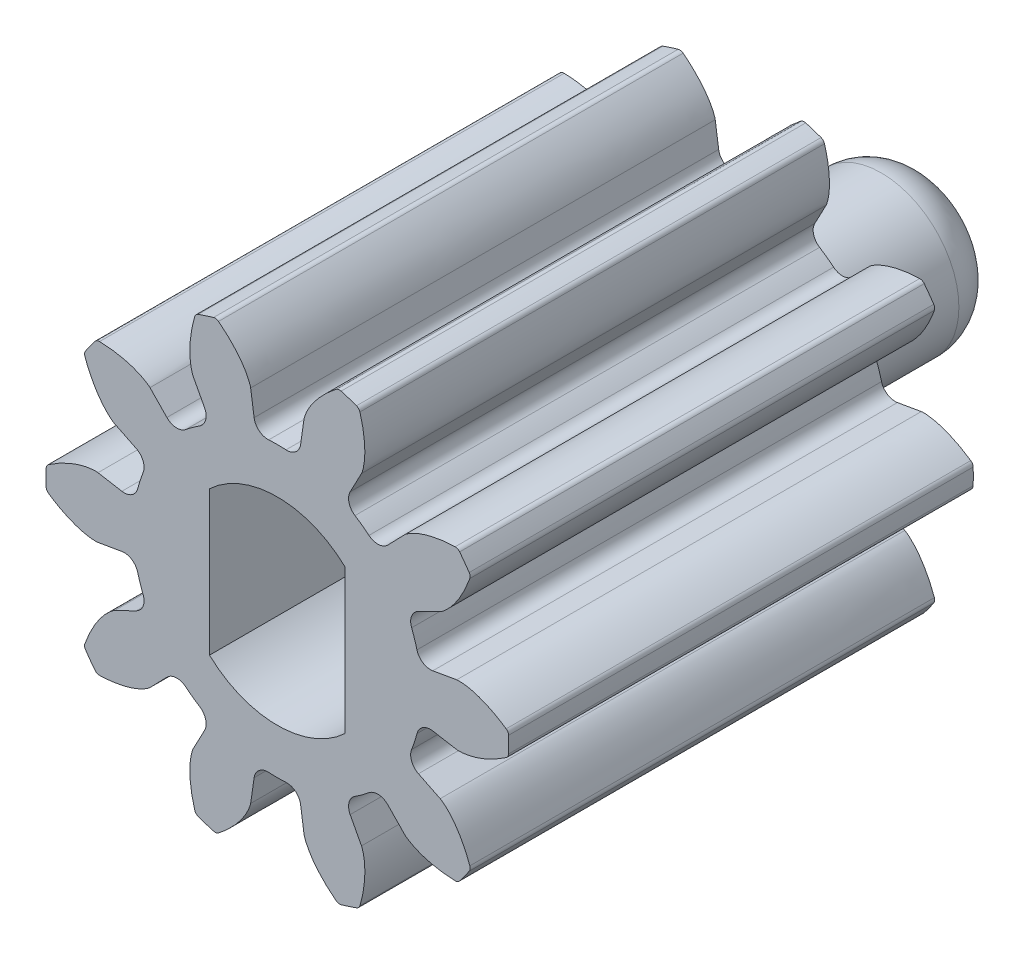
SolidWorks part; units mm, degrees
material "ABS"
ref_plane "Front" through (0, 0, 0) normal (0, 0, 1) x (1, 0, 0)
ref_plane "Top" through (0, 0, 0) normal (0, 1, 0) x (1, 0, 0)
ref_plane "Right" through (0, 0, 0) normal (1, 0, 0) x (0, 0, -1)
sketch "Sketch1" plane through (0, 0, 0) normal (0, 0, 1) x (1, 0, 0)
  circle A0 centre (0, 0) radius 6.35
extrude "Boss-Extrude1" add sketch "Sketch1" along normal blind 12.7
sketch "Sketch3" plane through (0, 0, 0) normal (0, 0, 1) x (1, 0, 0)
  line L0 (0, 0) -> (43.7181, 0) construction
  line L2 (0, 0) -> (-0.5624, 3.9287) construction
  line L3 (0, 0) -> (0.5624, 3.9287) construction
  line L4 (0.5624, 3.9287) -> (0.7046, 4.9224) construction
  line L5 (0, 0) -> (0, 61.276) construction
  line L6 (-0.5624, 3.9287) -> (-0.7046, 4.9224) construction
  circle A0 centre (0, 0) radius 6.35 construction
  circle A1 centre (0, 0) radius 5.2917 construction
  circle A2 centre (0, 0) radius 4.9725 construction
  arc A3 (0.5624, 3.9287) -> (-0.5624, 3.9287) centre (0, 0) ccw construction
  arc A5 (1.6642, 6.128) -> (-1.6642, 6.128) centre (0, 0) ccw
  spline S0 degree 4 poles (-0.7046, 4.9224) (-0.705, 4.9247) (-0.7061, 4.9311) (-0.7087, 4.9431) (-0.7137, 4.9626) (-0.721, 4.9872) (-0.7316, 5.0187) (-0.7454, 5.0554) (-0.7621, 5.0953) (-0.7818, 5.1381) (-0.8028, 5.1804) (-0.825, 5.2221) (-0.8483, 5.2631) (-0.8779, 5.3122) (-0.9151, 5.3703) (-0.9613, 5.437) (-1.0167, 5.511) (-1.0764, 5.5846) (-1.1378, 5.6556) (-1.2027, 5.7255) (-1.2676, 5.7919) (-1.338, 5.8588) (-1.4044, 5.9196) (-1.4819, 5.9855) (-1.5453, 6.0379) (-1.6323, 6.1046) (-1.6846, 6.1433) (-1.7469, 6.1876) (-1.7752, 6.2068) (-1.7925, 6.2186) knots 0 0 0 0 0 0.005377 0.015084 0.028532 0.04661 0.064855 0.092111 0.119476 0.146842 0.174209 0.201575 0.228941 0.256307 0.307035 0.361767 0.4165 0.471232 0.525964 0.580697 0.635429 0.690161 0.744894 0.799626 0.854358 0.909091 0.954545 1 1 1 1 1 construction
  spline S1 degree 4 poles (-0.7046, 4.9224) (-0.705, 4.9247) (-0.7061, 4.9311) (-0.7087, 4.9431) (-0.7137, 4.9626) (-0.721, 4.9872) (-0.7316, 5.0187) (-0.7454, 5.0554) (-0.7621, 5.0953) (-0.7818, 5.1381) (-0.8028, 5.1804) (-0.825, 5.2221) (-0.8483, 5.2631) (-0.8779, 5.3122) (-0.9151, 5.3703) (-0.9613, 5.437) (-1.0167, 5.511) (-1.0764, 5.5846) (-1.1378, 5.6556) (-1.2027, 5.7255) (-1.2676, 5.7919) (-1.338, 5.8588) (-1.4044, 5.9196) (-1.4819, 5.9855) (-1.5453, 6.0379) (-1.6134, 6.0902) (-1.647, 6.1153) (-1.6642, 6.128) knots 0 0 0 0 0 0.005377 0.015084 0.028532 0.04661 0.064855 0.092111 0.119476 0.146842 0.174209 0.201575 0.228941 0.256307 0.307035 0.361767 0.4165 0.471232 0.525964 0.580697 0.635429 0.690161 0.744894 0.799626 0.854358 0.909091 0.909091 0.909091 0.909091 0.909091
  spline S2 degree 4 poles (0.7046, 4.9224) (0.705, 4.9247) (0.7061, 4.9311) (0.7087, 4.9431) (0.7137, 4.9626) (0.721, 4.9872) (0.7316, 5.0187) (0.7454, 5.0554) (0.7621, 5.0953) (0.7818, 5.1381) (0.8028, 5.1804) (0.825, 5.2221) (0.8483, 5.2631) (0.8779, 5.3122) (0.9151, 5.3703) (0.9613, 5.437) (1.0167, 5.511) (1.0764, 5.5846) (1.1378, 5.6556) (1.2027, 5.7255) (1.2676, 5.7919) (1.338, 5.8588) (1.4044, 5.9196) (1.4819, 5.9855) (1.5453, 6.0379) (1.6323, 6.1046) (1.6846, 6.1433) (1.7469, 6.1876) (1.7752, 6.2068) (1.7925, 6.2186) knots 0 0 0 0 0 0.005377 0.015084 0.028532 0.04661 0.064855 0.092111 0.119476 0.146842 0.174209 0.201575 0.228941 0.256307 0.307035 0.361767 0.4165 0.471232 0.525964 0.580697 0.635429 0.690161 0.744894 0.799626 0.854358 0.909091 0.954545 1 1 1 1 1 construction
  spline S3 degree 4 poles (0.7046, 4.9224) (0.705, 4.9247) (0.7061, 4.9311) (0.7087, 4.9431) (0.7137, 4.9626) (0.721, 4.9872) (0.7316, 5.0187) (0.7454, 5.0554) (0.7621, 5.0953) (0.7818, 5.1381) (0.8028, 5.1804) (0.825, 5.2221) (0.8483, 5.2631) (0.8779, 5.3122) (0.9151, 5.3703) (0.9613, 5.437) (1.0167, 5.511) (1.0764, 5.5846) (1.1378, 5.6556) (1.2027, 5.7255) (1.2676, 5.7919) (1.338, 5.8588) (1.4044, 5.9196) (1.4819, 5.9855) (1.5453, 6.0379) (1.6134, 6.0902) (1.647, 6.1153) (1.6642, 6.128) knots 0 0 0 0 0 0.005377 0.015084 0.028532 0.04661 0.064855 0.092111 0.119476 0.146842 0.174209 0.201575 0.228941 0.256307 0.307035 0.361767 0.4165 0.471232 0.525964 0.580697 0.635429 0.690161 0.744894 0.799626 0.854358 0.909091 0.909091 0.909091 0.909091 0.909091
  point P0 (0, 3.9688)
sketch "DCLTBC" plane through (0, 0, 0) normal (0, 0, 1) x (1, 0, 0)
  line L0 (0, 0) -> (41.04, 0) construction
  line L1 (-0.5624, 3.9287) -> (-0.7046, 4.9224) construction
  line L2 (0.5624, 3.9287) -> (0.7046, 4.9224) construction
  line L3 (-0.5624, 3.9287) -> (-0.7046, 4.9224)
  line L4 (0.5624, 3.9287) -> (0.7046, 4.9224)
  line L5 (0, 0) -> (0, 104.9356) construction
  circle A0 centre (0, 0) radius 6.35
  circle A1 centre (0, 0) radius 5.2917 construction
  circle A2 centre (0, 0) radius 4.9725 construction
  arc A3 (0.5624, 3.9287) -> (-0.5624, 3.9287) centre (0, 0) ccw construction
  arc A4 (0.5624, 3.9287) -> (-0.5624, 3.9287) centre (0, 0) ccw
  spline S0 degree 4 poles (-988.7588, -149.038) (-11.8151, 2.4708) (-0.7866, 4.3496) (-0.6413, 4.6789) (-0.7137, 4.9626) (-0.721, 4.9872) (-0.7316, 5.0187) (-0.7454, 5.0554) (-0.7621, 5.0953) (-0.7818, 5.1381) (-0.8028, 5.1804) (-0.825, 5.2221) (-0.8483, 5.2631) (-0.8779, 5.3122) (-0.9151, 5.3703) (-0.9613, 5.437) (-1.0167, 5.511) (-1.0764, 5.5846) (-1.1378, 5.6556) (-1.2027, 5.7255) (-1.2676, 5.7919) (-1.338, 5.8588) (-1.4044, 5.9196) (-1.4819, 5.9855) (-1.8387, 6.2805) (-3.231, 7.2231) (17.05, -7.85) (-807.2758, 598.5552) knots -0.632257 -0.632257 -0.632257 -0.632257 -0.632257 0.005377 0.015084 0.028532 0.04661 0.064855 0.092111 0.119476 0.146842 0.174209 0.201575 0.228941 0.256307 0.307035 0.361767 0.4165 0.471232 0.525964 0.580697 0.635429 0.690161 0.744894 0.799626 0.854358 1.920904 1.920904 1.920904 1.920904 1.920904 only from (-0.7046, 4.9224) to (-1.6642, 6.128) construction
  spline S1 degree 4 poles (988.7588, -149.038) (11.8151, 2.4708) (0.7866, 4.3496) (0.6413, 4.6789) (0.7137, 4.9626) (0.721, 4.9872) (0.7316, 5.0187) (0.7454, 5.0554) (0.7621, 5.0953) (0.7818, 5.1381) (0.8028, 5.1804) (0.825, 5.2221) (0.8483, 5.2631) (0.8779, 5.3122) (0.9151, 5.3703) (0.9613, 5.437) (1.0167, 5.511) (1.0764, 5.5846) (1.1378, 5.6556) (1.2027, 5.7255) (1.2676, 5.7919) (1.338, 5.8588) (1.4044, 5.9196) (1.4819, 5.9855) (1.8387, 6.2805) (3.231, 7.2231) (-17.05, -7.85) (807.2758, 598.5552) knots -0.632257 -0.632257 -0.632257 -0.632257 -0.632257 0.005377 0.015084 0.028532 0.04661 0.064855 0.092111 0.119476 0.146842 0.174209 0.201575 0.228941 0.256307 0.307035 0.361767 0.4165 0.471232 0.525964 0.580697 0.635429 0.690161 0.744894 0.799626 0.854358 1.920904 1.920904 1.920904 1.920904 1.920904 only from (0.7046, 4.9224) to (1.6642, 6.128) construction
  spline S2 degree 4 poles (-0.7046, 4.9224) (-0.705, 4.9247) (-0.7061, 4.9311) (-0.7087, 4.9431) (-0.7137, 4.9626) (-0.721, 4.9872) (-0.7316, 5.0187) (-0.7454, 5.0554) (-0.7621, 5.0953) (-0.7818, 5.1381) (-0.8028, 5.1804) (-0.825, 5.2221) (-0.8483, 5.2631) (-0.8779, 5.3122) (-0.9151, 5.3703) (-0.9613, 5.437) (-1.0167, 5.511) (-1.0764, 5.5846) (-1.1378, 5.6556) (-1.2027, 5.7255) (-1.2676, 5.7919) (-1.338, 5.8588) (-1.4044, 5.9196) (-1.4819, 5.9855) (-1.5453, 6.0379) (-1.6134, 6.0902) (-1.647, 6.1153) (-1.6642, 6.128) knots 0 0 0 0 0 0.005377 0.015084 0.028532 0.04661 0.064855 0.092111 0.119476 0.146842 0.174209 0.201575 0.228941 0.256307 0.307035 0.361767 0.4165 0.471232 0.525964 0.580697 0.635429 0.690161 0.744894 0.799626 0.854358 0.909091 0.909091 0.909091 0.909091 0.909091
  spline S3 degree 4 poles (0.7046, 4.9224) (0.705, 4.9247) (0.7061, 4.9311) (0.7087, 4.9431) (0.7137, 4.9626) (0.721, 4.9872) (0.7316, 5.0187) (0.7454, 5.0554) (0.7621, 5.0953) (0.7818, 5.1381) (0.8028, 5.1804) (0.825, 5.2221) (0.8483, 5.2631) (0.8779, 5.3122) (0.9151, 5.3703) (0.9613, 5.437) (1.0167, 5.511) (1.0764, 5.5846) (1.1378, 5.6556) (1.2027, 5.7255) (1.2676, 5.7919) (1.338, 5.8588) (1.4044, 5.9196) (1.4819, 5.9855) (1.5453, 6.0379) (1.6134, 6.0902) (1.647, 6.1153) (1.6642, 6.128) knots 0 0 0 0 0 0.005377 0.015084 0.028532 0.04661 0.064855 0.092111 0.119476 0.146842 0.174209 0.201575 0.228941 0.256307 0.307035 0.361767 0.4165 0.471232 0.525964 0.580697 0.635429 0.690161 0.744894 0.799626 0.854358 0.909091 0.909091 0.909091 0.909091 0.909091
extrude "Cut-Extrude-DCLTBC" cut sketch "DCLTBC" along normal through all
fillet "Fillet-Tip-DCLTBC" radius 0.1775 2 edges at (1.6642, 6.128, 6.35) (-1.6642, 6.128, 6.35)
fillet "Fillet-Root-DCLTBC" radius 0.3551 2 edges at (-0.5624, 3.9287, 6.35) (0.5624, 3.9287, 6.35)
pattern_circular "CirPattern-DCLTBC" count 10 over 360 about axis through (0, 0, 12.7) along (0, 0, 1) of "Cut-Extrude-DCLTBC", "Fillet-Tip-DCLTBC", "Fillet-Root-DCLTBC"
sketch "DCGTBC" [suppressed] plane through (0, 0, 0) normal (0, 0, 1) x (1, 0, 0)
  line L0 (0, 0) -> (41.04, 0) construction
  line L1 (-22.6634, 1.9828) -> (0, 0) construction
  line L2 (0, 0) -> (22.6634, 1.9828) construction
  line L3 (0, 0) -> (-16.5124, 0)
  line L5 (0, 0) -> (0, 104.9356) construction
  circle A0 centre (0, 0) radius 25
  circle A1 centre (0, 0) radius 24 construction
  circle A2 centre (0, 0) radius 21.7514 construction
  arc A3 (0.0626, 22.7499) -> (-0.0626, 22.7499) centre (0, 0) ccw construction
  arc A11 (22.6634, 1.9828) -> (-22.6634, 1.9828) centre (0, 0) ccw
  spline S4 degree 4 poles (999.7589, -2.0808) (12.8658, 20.0937) (0.2547, 20.6746) (0.0189, 21.2606) (0.0654, 21.8429) (0.0715, 21.8997) (0.0812, 21.973) (0.095, 22.0592) (0.1126, 22.1539) (0.1343, 22.2566) (0.1583, 22.3589) (0.1845, 22.4607) (0.2124, 22.562) (0.2486, 22.6844) (0.2952, 22.8308) (0.3543, 23.0013) (0.4268, 23.1939) (0.5065, 23.3893) (0.5897, 23.5809) (0.6793, 23.7735) (0.7698, 23.9592) (0.8695, 24.151) (0.9643, 24.3275) (1.0767, 24.524) (1.517, 25.277) (3.0654, 27.5692) (-13.787, 0.9944) (540.7091, 867.0187) knots -0.561807 -0.561807 -0.561807 -0.561807 -0.561807 0.005377 0.015084 0.028532 0.04661 0.064855 0.092111 0.119476 0.146842 0.174209 0.201575 0.228941 0.256307 0.307035 0.361767 0.4165 0.471232 0.525964 0.580697 0.635429 0.690161 0.744894 0.799626 0.854358 1.731906 1.731906 1.731906 1.731906 1.731906 only from (0.0598, 21.7513) to (1.3455, 24.9638) construction
  spline S5 degree 4 poles (-999.7589, -2.0808) (-12.8658, 20.0937) (-0.2547, 20.6746) (-0.0189, 21.2606) (-0.0654, 21.8429) (-0.0715, 21.8997) (-0.0812, 21.973) (-0.095, 22.0592) (-0.1126, 22.1539) (-0.1343, 22.2566) (-0.1583, 22.3589) (-0.1845, 22.4607) (-0.2124, 22.562) (-0.2486, 22.6844) (-0.2952, 22.8308) (-0.3543, 23.0013) (-0.4268, 23.1939) (-0.5065, 23.3893) (-0.5897, 23.5809) (-0.6793, 23.7735) (-0.7698, 23.9592) (-0.8695, 24.151) (-0.9643, 24.3275) (-1.0767, 24.524) (-1.517, 25.277) (-3.0654, 27.5692) (13.787, 0.9944) (-540.7091, 867.0187) knots -0.561807 -0.561807 -0.561807 -0.561807 -0.561807 0.005377 0.015084 0.028532 0.04661 0.064855 0.092111 0.119476 0.146842 0.174209 0.201575 0.228941 0.256307 0.307035 0.361767 0.4165 0.471232 0.525964 0.580697 0.635429 0.690161 0.744894 0.799626 0.854358 1.731906 1.731906 1.731906 1.731906 1.731906 only from (-0.0598, 21.7513) to (-1.3455, 24.9638) construction
  spline S6 degree 4 poles (0.0598, 21.7513) (0.0599, 21.7565) (0.0603, 21.7709) (0.0618, 21.7983) (0.0654, 21.8429) (0.0715, 21.8997) (0.0812, 21.973) (0.095, 22.0592) (0.1126, 22.1539) (0.1343, 22.2566) (0.1583, 22.3589) (0.1845, 22.4607) (0.2124, 22.562) (0.2486, 22.6844) (0.2952, 22.8308) (0.3543, 23.0013) (0.4268, 23.1939) (0.5065, 23.3893) (0.5897, 23.5809) (0.6793, 23.7735) (0.7698, 23.9592) (0.8695, 24.151) (0.9643, 24.3275) (1.0767, 24.524) (1.1693, 24.6823) (1.27, 24.8447) (1.3197, 24.9235) (1.3455, 24.9638) knots 0 0 0 0 0 0.005377 0.015084 0.028532 0.04661 0.064855 0.092111 0.119476 0.146842 0.174209 0.201575 0.228941 0.256307 0.307035 0.361767 0.4165 0.471232 0.525964 0.580697 0.635429 0.690161 0.744894 0.799626 0.854358 0.909091 0.909091 0.909091 0.909091 0.909091
  spline S7 degree 4 poles (-0.0598, 21.7513) (-0.0599, 21.7565) (-0.0603, 21.7709) (-0.0618, 21.7983) (-0.0654, 21.8429) (-0.0715, 21.8997) (-0.0812, 21.973) (-0.095, 22.0592) (-0.1126, 22.1539) (-0.1343, 22.2566) (-0.1583, 22.3589) (-0.1845, 22.4607) (-0.2124, 22.562) (-0.2486, 22.6844) (-0.2952, 22.8308) (-0.3543, 23.0013) (-0.4268, 23.1939) (-0.5065, 23.3893) (-0.5897, 23.5809) (-0.6793, 23.7735) (-0.7698, 23.9592) (-0.8695, 24.151) (-0.9643, 24.3275) (-1.0767, 24.524) (-1.1693, 24.6823) (-1.27, 24.8447) (-1.3197, 24.9235) (-1.3455, 24.9638) knots 0 0 0 0 0 0.005377 0.015084 0.028532 0.04661 0.064855 0.092111 0.119476 0.146842 0.174209 0.201575 0.228941 0.256307 0.307035 0.361767 0.4165 0.471232 0.525964 0.580697 0.635429 0.690161 0.744894 0.799626 0.854358 0.909091 0.909091 0.909091 0.909091 0.909091
  dimension "D1" = 5
  dimension "D2" = 5
extrude "Cut-Extrude-DCGTBC" [suppressed] cut sketch "DCGTBC" along normal through all
fillet "Fillet-Tip-DCGTBC" [suppressed] radius 0.1775
pattern_circular "CirPattern-DCGTBC" [suppressed] count 10 over 360
sketch "Sketch4" plane through (0, 0, 12.7) normal (0, 0, 1) x (1, 0, 0)
  circle A1 centre (0, 0) radius 2.7051
  dimension "D1" = 5.4102
extrude "Cut-Extrude2" cut sketch "Sketch4" against normal through all
sketch "Sketch5" plane through (0, 0, 12.7) normal (0, 0, 1) x (1, 0, 0)
  line L0 (-1.8542, 1.9696) -> (-1.8542, -1.9696)
  line L1 (1.8542, 1.9696) -> (1.8542, -1.9696)
  circle A0 centre (0, 0) radius 2.7051 construction
  circle A1 centre (0, 0) radius 2.7051
  dimension "D1" = 3.7084
extrude "Boss-Extrude2" add sketch "Sketch5" against normal through all contours L0 A1 | L1 A1
sketch "Sketch6" plane through (0, 0, 0) normal (0, 0, -1) x (-1, 0, 0)
  line L4 (-1.9655, 2.0878) -> (-1.9655, -2.0878)
  line L5 (1.9655, -2.0878) -> (1.9655, 2.0878)
  arc A4 (-1.9655, -2.0878) -> (1.9655, -2.0878) centre (0, 0) ccw
  arc A5 (1.9655, 2.0878) -> (-1.9655, 2.0878) centre (0, 0) ccw
extrude "Boss-Extrude3" add sketch "Sketch6" against normal blind 3.175
sketch "Sketch7" plane through (0, 0, 0) normal (0, 0, -1) x (-1, 0, 0)
  circle A0 centre (0, 0) radius 2.1209
  dimension "D1" = 4.2418
extrude "Boss-Extrude4" add sketch "Sketch7" along normal blind 5.08
fillet "Fillet1" radius 1.27 1 edges at (-2.1209, 0, -5.08)
sketch "Sketch8" plane through (0, 0, 12.7) normal (0, 0, 1) x (1, 0, 0)
  line L50 (0.7297, 4.9185) -> (0.6357, 4.2621)
  line L51 (-0.6357, 4.2621) -> (-0.7297, 4.9185)
  line L52 (-2.3007, 4.4081) -> (-1.9909, 3.8218)
  line L53 (-3.0196, 3.0745) -> (-3.4814, 3.5503)
  line L54 (-4.4523, 2.2139) -> (-3.8571, 1.9217)
  line L55 (-4.25, 0.7124) -> (-4.9033, 0.8259)
  line L56 (-4.9033, -0.8259) -> (-4.25, -0.7124)
  line L57 (-3.8571, -1.9217) -> (-4.4523, -2.2139)
  line L58 (-3.4814, -3.5503) -> (-3.0196, -3.0745)
  line L59 (-1.9909, -3.8218) -> (-2.3007, -4.4081)
  line L60 (-0.7297, -4.9185) -> (-0.6357, -4.2621)
  line L61 (0.6357, -4.2621) -> (0.7297, -4.9185)
  line L62 (2.3007, -4.4081) -> (1.9909, -3.8218)
  line L63 (3.0196, -3.0745) -> (3.4814, -3.5503)
  line L64 (4.4523, -2.2139) -> (3.8571, -1.9217)
  line L65 (4.25, -0.7124) -> (4.9033, -0.8259)
  line L66 (4.9033, 0.8259) -> (4.25, 0.7124)
  line L67 (3.8571, 1.9217) -> (4.4523, 2.2139)
  line L68 (3.4814, 3.5503) -> (3.0196, 3.0745)
  line L69 (1.9909, 3.8218) -> (2.3007, 4.4081)
  line L74 (0.7297, 4.9185) -> (0.6357, 4.2621)
  line L75 (-0.6357, 4.2621) -> (-0.7297, 4.9185)
  line L76 (-2.3007, 4.4081) -> (-1.9909, 3.8218)
  line L77 (-3.0196, 3.0745) -> (-3.4814, 3.5503)
  line L78 (-4.4523, 2.2139) -> (-3.8571, 1.9217)
  line L79 (-4.25, 0.7124) -> (-4.9033, 0.8259)
  line L80 (-4.9033, -0.8259) -> (-4.25, -0.7124)
  line L81 (-3.8571, -1.9217) -> (-4.4523, -2.2139)
  line L82 (-3.4814, -3.5503) -> (-3.0196, -3.0745)
  line L83 (-1.9909, -3.8218) -> (-2.3007, -4.4081)
  line L84 (-0.7297, -4.9185) -> (-0.6357, -4.2621)
  line L85 (0.6357, -4.2621) -> (0.7297, -4.9185)
  line L86 (2.3007, -4.4081) -> (1.9909, -3.8218)
  line L87 (3.0196, -3.0745) -> (3.4814, -3.5503)
  line L88 (4.4523, -2.2139) -> (3.8571, -1.9217)
  line L89 (4.25, -0.7124) -> (4.9033, -0.8259)
  line L90 (4.9033, 0.8259) -> (4.25, 0.7124)
  line L91 (3.8571, 1.9217) -> (4.4523, 2.2139)
  line L92 (3.4814, 3.5503) -> (3.0196, 3.0745)
  line L93 (1.9909, 3.8218) -> (2.3007, 4.4081)
  arc A150 (2.1634, 5.9431) -> (1.743, 6.0797) centre (0, 0) ccw
  arc A151 (1.743, 6.0797) -> (1.6082, 6.054) centre (1.7011, 5.9334) ccw
  arc A152 (0.2363, 3.9363) -> (0.6357, 4.2621) centre (0.2591, 4.3161) ccw
  arc A153 (0.2363, 3.9363) -> (-0.2363, 3.9363) centre (0, 0) ccw
  arc A154 (-0.6357, 4.2621) -> (-0.2363, 3.9363) centre (-0.2591, 4.3161) ccw
  arc A155 (-1.6082, 6.054) -> (-1.743, 6.0797) centre (-1.7011, 5.9334) ccw
  arc A156 (-1.743, 6.0797) -> (-2.1634, 5.9431) centre (0, 0) ccw
  arc A157 (-2.1634, 5.9431) -> (-2.2573, 5.8431) centre (-2.1114, 5.8001) ccw
  arc A158 (-2.1225, 3.3234) -> (-1.9909, 3.8218) centre (-2.3273, 3.6441) ccw
  arc A159 (-2.1225, 3.3234) -> (-2.5049, 3.0456) centre (0, 0) ccw
  arc A160 (-3.0196, 3.0745) -> (-2.5049, 3.0456) centre (-2.7465, 3.3395) ccw
  arc A161 (-4.8595, 3.9525) -> (-4.9837, 3.894) centre (-4.8638, 3.8004) ccw
  arc A162 (-4.9837, 3.894) -> (-5.2435, 3.5364) centre (0, 0) ccw
  arc A163 (-5.2435, 3.5364) -> (-5.2607, 3.4003) centre (-5.1174, 3.4514) ccw
  arc A164 (-3.6706, 1.4411) -> (-3.8571, 1.9217) centre (-4.0247, 1.5802) ccw
  arc A165 (-3.6706, 1.4411) -> (-3.8166, 0.9916) centre (0, 0) ccw
  arc A166 (-4.25, 0.7124) -> (-3.8166, 0.9916) centre (-4.1849, 1.0873) ccw
  arc A167 (-6.2546, 0.3412) -> (-6.3207, 0.221) centre (-6.1687, 0.2157) ccw
  arc A168 (-6.3207, 0.221) -> (-6.3207, -0.221) centre (0, 0) ccw
  arc A169 (-6.3207, -0.221) -> (-6.2546, -0.3412) centre (-6.1687, -0.2157) ccw
  arc A170 (-3.8166, -0.9916) -> (-4.25, -0.7124) centre (-4.1849, -1.0873) ccw
  arc A171 (-3.8166, -0.9916) -> (-3.6706, -1.4411) centre (0, 0) ccw
  arc A172 (-3.8571, -1.9217) -> (-3.6706, -1.4411) centre (-4.0247, -1.5802) ccw
  arc A173 (-5.2607, -3.4003) -> (-5.2435, -3.5364) centre (-5.1174, -3.4514) ccw
  arc A174 (-5.2435, -3.5364) -> (-4.9837, -3.894) centre (0, 0) ccw
  arc A175 (-4.9837, -3.894) -> (-4.8595, -3.9525) centre (-4.8638, -3.8004) ccw
  arc A176 (-2.5049, -3.0456) -> (-3.0196, -3.0745) centre (-2.7465, -3.3395) ccw
  arc A177 (-2.5049, -3.0456) -> (-2.1225, -3.3234) centre (0, 0) ccw
  arc A178 (-1.9909, -3.8218) -> (-2.1225, -3.3234) centre (-2.3273, -3.6441) ccw
  arc A179 (-2.2573, -5.8431) -> (-2.1634, -5.9431) centre (-2.1114, -5.8001) ccw
  arc A180 (-2.1634, -5.9431) -> (-1.743, -6.0797) centre (0, 0) ccw
  arc A181 (-1.743, -6.0797) -> (-1.6082, -6.054) centre (-1.7011, -5.9334) ccw
  arc A182 (-0.2363, -3.9363) -> (-0.6357, -4.2621) centre (-0.2591, -4.3161) ccw
  arc A183 (-0.2363, -3.9363) -> (0.2363, -3.9363) centre (0, 0) ccw
  arc A184 (0.6357, -4.2621) -> (0.2363, -3.9363) centre (0.2591, -4.3161) ccw
  arc A185 (1.6082, -6.054) -> (1.743, -6.0797) centre (1.7011, -5.9334) ccw
  arc A186 (1.743, -6.0797) -> (2.1634, -5.9431) centre (0, 0) ccw
  arc A187 (2.1634, -5.9431) -> (2.2573, -5.8431) centre (2.1114, -5.8001) ccw
  arc A188 (2.1225, -3.3234) -> (1.9909, -3.8218) centre (2.3273, -3.6441) ccw
  arc A189 (2.1225, -3.3234) -> (2.5049, -3.0456) centre (0, 0) ccw
  arc A190 (3.0196, -3.0745) -> (2.5049, -3.0456) centre (2.7465, -3.3395) ccw
  arc A191 (4.8595, -3.9525) -> (4.9837, -3.894) centre (4.8638, -3.8004) ccw
  arc A192 (4.9837, -3.894) -> (5.2435, -3.5364) centre (0, 0) ccw
  arc A193 (5.2435, -3.5364) -> (5.2607, -3.4003) centre (5.1174, -3.4514) ccw
  arc A194 (3.6706, -1.4411) -> (3.8571, -1.9217) centre (4.0247, -1.5802) ccw
  arc A195 (3.6706, -1.4411) -> (3.8166, -0.9916) centre (0, 0) ccw
  arc A196 (4.25, -0.7124) -> (3.8166, -0.9916) centre (4.1849, -1.0873) ccw
  arc A197 (6.2546, -0.3412) -> (6.3207, -0.221) centre (6.1687, -0.2157) ccw
  arc A198 (6.3207, -0.221) -> (6.3207, 0.221) centre (0, 0) ccw
  arc A199 (6.3207, 0.221) -> (6.2546, 0.3412) centre (6.1687, 0.2157) ccw
  arc A200 (3.8166, 0.9916) -> (4.25, 0.7124) centre (4.1849, 1.0873) ccw
  arc A201 (3.8166, 0.9916) -> (3.6706, 1.4411) centre (0, 0) ccw
  arc A202 (3.8571, 1.9217) -> (3.6706, 1.4411) centre (4.0247, 1.5802) ccw
  arc A203 (5.2607, 3.4003) -> (5.2435, 3.5364) centre (5.1174, 3.4514) ccw
  arc A204 (5.2435, 3.5364) -> (4.9837, 3.894) centre (0, 0) ccw
  arc A205 (4.9837, 3.894) -> (4.8595, 3.9525) centre (4.8638, 3.8004) ccw
  arc A206 (2.5049, 3.0456) -> (3.0196, 3.0745) centre (2.7465, 3.3395) ccw
  arc A207 (2.5049, 3.0456) -> (2.1225, 3.3234) centre (0, 0) ccw
  arc A208 (1.9909, 3.8218) -> (2.1225, 3.3234) centre (2.3273, 3.6441) ccw
  arc A209 (2.2573, 5.8431) -> (2.1634, 5.9431) centre (2.1114, 5.8001) ccw
  arc A222 (2.1634, 5.9431) -> (1.743, 6.0797) centre (0, 0) ccw
  arc A223 (1.743, 6.0797) -> (1.6082, 6.054) centre (1.7011, 5.9334) ccw
  arc A224 (0.2363, 3.9363) -> (0.6357, 4.2621) centre (0.2591, 4.3161) ccw
  arc A225 (0.2363, 3.9363) -> (-0.2363, 3.9363) centre (0, 0) ccw
  arc A226 (-0.6357, 4.2621) -> (-0.2363, 3.9363) centre (-0.2591, 4.3161) ccw
  arc A227 (-1.6082, 6.054) -> (-1.743, 6.0797) centre (-1.7011, 5.9334) ccw
  arc A228 (-1.743, 6.0797) -> (-2.1634, 5.9431) centre (0, 0) ccw
  arc A229 (-2.1634, 5.9431) -> (-2.2573, 5.8431) centre (-2.1114, 5.8001) ccw
  arc A230 (-2.1225, 3.3234) -> (-1.9909, 3.8218) centre (-2.3273, 3.6441) ccw
  arc A231 (-2.1225, 3.3234) -> (-2.5049, 3.0456) centre (0, 0) ccw
  arc A232 (-3.0196, 3.0745) -> (-2.5049, 3.0456) centre (-2.7465, 3.3395) ccw
  arc A233 (-4.8595, 3.9525) -> (-4.9837, 3.894) centre (-4.8638, 3.8004) ccw
  arc A234 (-4.9837, 3.894) -> (-5.2435, 3.5364) centre (0, 0) ccw
  arc A235 (-5.2435, 3.5364) -> (-5.2607, 3.4003) centre (-5.1174, 3.4514) ccw
  arc A236 (-3.6706, 1.4411) -> (-3.8571, 1.9217) centre (-4.0247, 1.5802) ccw
  arc A237 (-3.6706, 1.4411) -> (-3.8166, 0.9916) centre (0, 0) ccw
  arc A238 (-4.25, 0.7124) -> (-3.8166, 0.9916) centre (-4.1849, 1.0873) ccw
  arc A239 (-6.2546, 0.3412) -> (-6.3207, 0.221) centre (-6.1687, 0.2157) ccw
  arc A240 (-6.3207, 0.221) -> (-6.3207, -0.221) centre (0, 0) ccw
  arc A241 (-6.3207, -0.221) -> (-6.2546, -0.3412) centre (-6.1687, -0.2157) ccw
  arc A242 (-3.8166, -0.9916) -> (-4.25, -0.7124) centre (-4.1849, -1.0873) ccw
  arc A243 (-3.8166, -0.9916) -> (-3.6706, -1.4411) centre (0, 0) ccw
  arc A244 (-3.8571, -1.9217) -> (-3.6706, -1.4411) centre (-4.0247, -1.5802) ccw
  arc A245 (-5.2607, -3.4003) -> (-5.2435, -3.5364) centre (-5.1174, -3.4514) ccw
  arc A246 (-5.2435, -3.5364) -> (-4.9837, -3.894) centre (0, 0) ccw
  arc A247 (-4.9837, -3.894) -> (-4.8595, -3.9525) centre (-4.8638, -3.8004) ccw
  arc A248 (-2.5049, -3.0456) -> (-3.0196, -3.0745) centre (-2.7465, -3.3395) ccw
  arc A249 (-2.5049, -3.0456) -> (-2.1225, -3.3234) centre (0, 0) ccw
  arc A250 (-1.9909, -3.8218) -> (-2.1225, -3.3234) centre (-2.3273, -3.6441) ccw
  arc A251 (-2.2573, -5.8431) -> (-2.1634, -5.9431) centre (-2.1114, -5.8001) ccw
  arc A252 (-2.1634, -5.9431) -> (-1.743, -6.0797) centre (0, 0) ccw
  arc A253 (-1.743, -6.0797) -> (-1.6082, -6.054) centre (-1.7011, -5.9334) ccw
  arc A254 (-0.2363, -3.9363) -> (-0.6357, -4.2621) centre (-0.2591, -4.3161) ccw
  arc A255 (-0.2363, -3.9363) -> (0.2363, -3.9363) centre (0, 0) ccw
  arc A256 (0.6357, -4.2621) -> (0.2363, -3.9363) centre (0.2591, -4.3161) ccw
  arc A257 (1.6082, -6.054) -> (1.743, -6.0797) centre (1.7011, -5.9334) ccw
  arc A258 (1.743, -6.0797) -> (2.1634, -5.9431) centre (0, 0) ccw
  arc A259 (2.1634, -5.9431) -> (2.2573, -5.8431) centre (2.1114, -5.8001) ccw
  arc A260 (2.1225, -3.3234) -> (1.9909, -3.8218) centre (2.3273, -3.6441) ccw
  arc A261 (2.1225, -3.3234) -> (2.5049, -3.0456) centre (0, 0) ccw
  arc A262 (3.0196, -3.0745) -> (2.5049, -3.0456) centre (2.7465, -3.3395) ccw
  arc A263 (4.8595, -3.9525) -> (4.9837, -3.894) centre (4.8638, -3.8004) ccw
  arc A264 (4.9837, -3.894) -> (5.2435, -3.5364) centre (0, 0) ccw
  arc A265 (5.2435, -3.5364) -> (5.2607, -3.4003) centre (5.1174, -3.4514) ccw
  arc A266 (3.6706, -1.4411) -> (3.8571, -1.9217) centre (4.0247, -1.5802) ccw
  arc A267 (3.6706, -1.4411) -> (3.8166, -0.9916) centre (0, 0) ccw
  arc A268 (4.25, -0.7124) -> (3.8166, -0.9916) centre (4.1849, -1.0873) ccw
  arc A269 (6.2546, -0.3412) -> (6.3207, -0.221) centre (6.1687, -0.2157) ccw
  arc A270 (6.3207, -0.221) -> (6.3207, 0.221) centre (0, 0) ccw
  arc A271 (6.3207, 0.221) -> (6.2546, 0.3412) centre (6.1687, 0.2157) ccw
  arc A272 (3.8166, 0.9916) -> (4.25, 0.7124) centre (4.1849, 1.0873) ccw
  arc A273 (3.8166, 0.9916) -> (3.6706, 1.4411) centre (0, 0) ccw
  arc A274 (3.8571, 1.9217) -> (3.6706, 1.4411) centre (4.0247, 1.5802) ccw
  arc A275 (5.2607, 3.4003) -> (5.2435, 3.5364) centre (5.1174, 3.4514) ccw
  arc A276 (5.2435, 3.5364) -> (4.9837, 3.894) centre (0, 0) ccw
  arc A277 (4.9837, 3.894) -> (4.8595, 3.9525) centre (4.8638, 3.8004) ccw
  arc A278 (2.5049, 3.0456) -> (3.0196, 3.0745) centre (2.7465, 3.3395) ccw
  arc A279 (2.5049, 3.0456) -> (2.1225, 3.3234) centre (0, 0) ccw
  arc A280 (1.9909, 3.8218) -> (2.1225, 3.3234) centre (2.3273, 3.6441) ccw
  arc A281 (2.2573, 5.8431) -> (2.1634, 5.9431) centre (2.1114, 5.8001) ccw
  spline S50 degree 3 poles (-2981.1226, 322.9869) (138.6336, -64.8997) (11.7316, 18.4787) (1.005, 5.4571) (0.9336, 5.3577) (0.8415, 5.2008) (0.8133, 5.1471) (0.7762, 5.0638) (0.7647, 5.0354) (-0.1197, 2.5272) (1.8075, -0.8005) (2869.2547, -871.9201) knots -33.999078 -33.999078 -33.999078 -33.999078 0.5 0.5 0.75 0.75 0.875 0.875 0.9375 0.9375 6.320462 6.320462 6.320462 6.320462 only from (1.6082, 6.054) to (0.7297, 4.9185)
  spline S51 degree 3 poles (-2814.1262, -1035.4767) (-1.5149, -0.8224) (0.1127, 2.55) (-0.7648, 5.0357) (-0.7763, 5.0639) (-0.8136, 5.1477) (-0.8422, 5.202) (-0.9344, 5.359) (-1.005, 5.4571) (-11.3131, 17.9741) (-133.6801, -53.9624) (2992.326, -173.0623) knots -5.275059 -5.275059 -5.275059 -5.275059 0.0625 0.0625 0.125 0.125 0.25 0.25 0.5 0.5 33.744281 33.744281 33.744281 33.744281 only from (-0.7297, 4.9185) to (-1.6082, 6.054)
  spline S52 degree 3 poles (-2601.6258, -1490.958) (150.3041, 28.9818) (-1.3704, 21.8453) (-2.3945, 5.0056) (-2.3939, 4.8833) (-2.3761, 4.7021) (-2.3674, 4.6421) (-2.3484, 4.5529) (-2.3411, 4.5232) (-1.5823, 1.9742) (1.9329, 0.4148) (2833.7776, 981.1074) knots -33.999078 -33.999078 -33.999078 -33.999078 0.5 0.5 0.75 0.75 0.875 0.875 0.9375 0.9375 6.320462 6.320462 6.320462 6.320462 only from (-2.2573, 5.8431) to (-2.3007, 4.4081)
  spline S53 degree 3 poles (-1668.038, -2491.8202) (-0.7422, -1.5558) (-1.4076, 2.1292) (-3.5786, 3.6244) (-3.6045, 3.6405) (-3.684, 3.6864) (-3.739, 3.7135) (-3.9059, 3.7863) (-4.0207, 3.8242) (-19.7174, 7.8917) (-76.4312, -122.2317) (2522.566, 1618.8348) knots -5.275059 -5.275059 -5.275059 -5.275059 0.0625 0.0625 0.125 0.125 0.25 0.25 0.5 0.5 33.744281 33.744281 33.744281 33.744281 only from (-3.4814, 3.5503) to (-4.8595, 3.9525)
  spline S54 degree 3 poles (-1228.3963, -2735.4076) (104.5635, 111.7933) (-13.949, 16.8677) (-4.8795, 2.6422) (-4.807, 2.5435) (-4.6862, 2.4075) (-4.6439, 2.364) (-4.5761, 2.303) (-4.5526, 2.2833) (-2.4405, 0.6671) (1.3199, 1.4717) (1715.8938, 2459.3853) knots -33.999078 -33.999078 -33.999078 -33.999078 0.5 0.5 0.75 0.75 0.875 0.875 0.9375 0.9375 6.320462 6.320462 6.320462 6.320462 only from (-5.2607, 3.4003) to (-4.4523, 2.2139)
  spline S55 degree 3 poles (115.1841, -2996.373) (0.314, -1.6949) (-2.3903, 0.8952) (-5.0255, 0.8287) (-5.056, 0.8266) (-5.1472, 0.817) (-5.2077, 0.8065) (-5.3855, 0.7673) (-5.5006, 0.7305) (-20.5904, -5.2051) (10.0118, -143.8127) (1089.2716, 2792.3919) knots -5.275059 -5.275059 -5.275059 -5.275059 0.0625 0.0625 0.125 0.125 0.25 0.25 0.5 0.5 33.744281 33.744281 33.744281 33.744281 only from (-4.9033, 0.8259) to (-6.2546, 0.3412)
  spline S56 degree 3 poles (614.0388, -2935.0245) (18.8832, 151.9035) (-21.1996, 5.4472) (-5.5006, -0.7305) (-5.384, -0.7677) (-5.2063, -0.8068) (-5.1465, -0.8171) (-5.0558, -0.8266) (-5.0253, -0.8288) (-2.3666, -0.8948) (0.2028, 1.9664) (-57.4032, 2998.2615) knots -33.999078 -33.999078 -33.999078 -33.999078 0.5 0.5 0.75 0.75 0.875 0.875 0.9375 0.9375 6.320462 6.320462 6.320462 6.320462 only from (-6.2546, -0.3412) to (-4.9033, -0.8259)
  spline S57 degree 3 poles (1854.4097, -2356.4131) (1.2503, -1.1867) (-2.46, -0.6808) (-4.5529, -2.2835) (-4.5762, -2.3031) (-4.6444, -2.3645) (-4.6872, -2.4085) (-4.808, -2.5447) (-4.8794, -2.6421) (-13.5985, -16.3137) (92.6307, -110.4621) (-760.0876, 2899.3503) knots -5.275059 -5.275059 -5.275059 -5.275059 0.0625 0.0625 0.125 0.125 0.25 0.25 0.5 0.5 33.744281 33.744281 33.744281 33.744281 only from (-4.4523, -2.2139) to (-5.2607, -3.4003)
  spline S58 degree 3 poles (2221.9319, -2013.5618) (-74.0099, 133.9918) (-20.3526, -8.0539) (-4.0207, -3.8242) (-3.9045, -3.7858) (-3.7377, -3.7129) (-3.6834, -3.6861) (-3.6044, -3.6404) (-3.5784, -3.6242) (-1.3886, -2.1149) (-0.9918, 1.7101) (-1808.774, 2391.9038) knots -33.999078 -33.999078 -33.999078 -33.999078 0.5 0.5 0.75 0.75 0.875 0.875 0.9375 0.9375 6.320462 6.320462 6.320462 6.320462 only from (-4.8595, -3.9525) to (-3.4814, -3.5503)
  spline S59 degree 3 poles (2885.3139, -816.3836) (1.709, -0.2252) (-1.59, -1.9967) (-2.3412, -4.5235) (-2.3485, -4.5531) (-2.3676, -4.6428) (-2.3763, -4.7036) (-2.394, -4.8848) (-2.3945, -5.0056) (-1.4125, -21.191) (139.8678, -34.9187) (-2319.1191, 1898.8554) knots -5.275059 -5.275059 -5.275059 -5.275059 0.0625 0.0625 0.125 0.125 0.25 0.25 0.5 0.5 33.744281 33.744281 33.744281 33.744281 only from (-2.3007, -4.4081) to (-2.2573, -5.8431)
  spline S60 degree 3 poles (2981.1226, -322.9869) (-138.6336, 64.8997) (-11.7316, -18.4787) (-1.005, -5.4571) (-0.9336, -5.3577) (-0.8415, -5.2008) (-0.8133, -5.1471) (-0.7762, -5.0638) (-0.7647, -5.0354) (0.1197, -2.5272) (-1.8075, 0.8005) (-2869.2547, 871.9201) knots -33.999078 -33.999078 -33.999078 -33.999078 0.5 0.5 0.75 0.75 0.875 0.875 0.9375 0.9375 6.320462 6.320462 6.320462 6.320462 only from (-1.6082, -6.054) to (-0.7297, -4.9185)
  spline S61 degree 3 poles (2814.1262, 1035.4767) (1.5149, 0.8224) (-0.1127, -2.55) (0.7648, -5.0357) (0.7763, -5.0639) (0.8136, -5.1477) (0.8422, -5.202) (0.9344, -5.359) (1.005, -5.4571) (11.3131, -17.9741) (133.6801, 53.9624) (-2992.326, 173.0623) knots -5.275059 -5.275059 -5.275059 -5.275059 0.0625 0.0625 0.125 0.125 0.25 0.25 0.5 0.5 33.744281 33.744281 33.744281 33.744281 only from (0.7297, -4.9185) to (1.6082, -6.054)
  spline S62 degree 3 poles (2601.6258, 1490.958) (-150.3041, -28.9818) (1.3704, -21.8453) (2.3945, -5.0056) (2.3939, -4.8833) (2.3761, -4.7021) (2.3674, -4.6421) (2.3484, -4.5529) (2.3411, -4.5232) (1.5823, -1.9742) (-1.9329, -0.4148) (-2833.7776, -981.1074) knots -33.999078 -33.999078 -33.999078 -33.999078 0.5 0.5 0.75 0.75 0.875 0.875 0.9375 0.9375 6.320462 6.320462 6.320462 6.320462 only from (2.2573, -5.8431) to (2.3007, -4.4081)
  spline S63 degree 3 poles (1668.038, 2491.8202) (0.7422, 1.5558) (1.4076, -2.1292) (3.5786, -3.6244) (3.6045, -3.6405) (3.684, -3.6864) (3.739, -3.7135) (3.9059, -3.7863) (4.0207, -3.8242) (19.7174, -7.8917) (76.4312, 122.2317) (-2522.566, -1618.8348) knots -5.275059 -5.275059 -5.275059 -5.275059 0.0625 0.0625 0.125 0.125 0.25 0.25 0.5 0.5 33.744281 33.744281 33.744281 33.744281 only from (3.4814, -3.5503) to (4.8595, -3.9525)
  spline S64 degree 3 poles (1228.3963, 2735.4076) (-104.5635, -111.7933) (13.949, -16.8677) (4.8795, -2.6422) (4.807, -2.5435) (4.6862, -2.4075) (4.6439, -2.364) (4.5761, -2.303) (4.5526, -2.2833) (2.4405, -0.6671) (-1.3199, -1.4717) (-1715.8938, -2459.3853) knots -33.999078 -33.999078 -33.999078 -33.999078 0.5 0.5 0.75 0.75 0.875 0.875 0.9375 0.9375 6.320462 6.320462 6.320462 6.320462 only from (5.2607, -3.4003) to (4.4523, -2.2139)
  spline S65 degree 3 poles (-115.1841, 2996.373) (-0.314, 1.6949) (2.3903, -0.8952) (5.0255, -0.8287) (5.056, -0.8266) (5.1472, -0.817) (5.2077, -0.8065) (5.3855, -0.7673) (5.5006, -0.7305) (20.5904, 5.2051) (-10.0118, 143.8127) (-1089.2716, -2792.3919) knots -5.275059 -5.275059 -5.275059 -5.275059 0.0625 0.0625 0.125 0.125 0.25 0.25 0.5 0.5 33.744281 33.744281 33.744281 33.744281 only from (4.9033, -0.8259) to (6.2546, -0.3412)
  spline S66 degree 3 poles (-614.0388, 2935.0245) (-18.8832, -151.9035) (21.1996, -5.4472) (5.5006, 0.7305) (5.384, 0.7677) (5.2063, 0.8068) (5.1465, 0.8171) (5.0558, 0.8266) (5.0253, 0.8288) (2.3666, 0.8948) (-0.2028, -1.9664) (57.4032, -2998.2615) knots -33.999078 -33.999078 -33.999078 -33.999078 0.5 0.5 0.75 0.75 0.875 0.875 0.9375 0.9375 6.320462 6.320462 6.320462 6.320462 only from (6.2546, 0.3412) to (4.9033, 0.8259)
  spline S67 degree 3 poles (-1854.4097, 2356.4131) (-1.2503, 1.1867) (2.46, 0.6808) (4.5529, 2.2835) (4.5762, 2.3031) (4.6444, 2.3645) (4.6872, 2.4085) (4.808, 2.5447) (4.8794, 2.6421) (13.5985, 16.3137) (-92.6307, 110.4621) (760.0876, -2899.3503) knots -5.275059 -5.275059 -5.275059 -5.275059 0.0625 0.0625 0.125 0.125 0.25 0.25 0.5 0.5 33.744281 33.744281 33.744281 33.744281 only from (4.4523, 2.2139) to (5.2607, 3.4003)
  spline S68 degree 3 poles (-2221.9319, 2013.5618) (74.0099, -133.9918) (20.3526, 8.0539) (4.0207, 3.8242) (3.9045, 3.7858) (3.7377, 3.7129) (3.6834, 3.6861) (3.6044, 3.6404) (3.5784, 3.6242) (1.3886, 2.1149) (0.9918, -1.7101) (1808.774, -2391.9038) knots -33.999078 -33.999078 -33.999078 -33.999078 0.5 0.5 0.75 0.75 0.875 0.875 0.9375 0.9375 6.320462 6.320462 6.320462 6.320462 only from (4.8595, 3.9525) to (3.4814, 3.5503)
  spline S69 degree 3 poles (-2885.3139, 816.3836) (-1.709, 0.2252) (1.59, 1.9967) (2.3412, 4.5235) (2.3485, 4.5531) (2.3676, 4.6428) (2.3763, 4.7036) (2.394, 4.8848) (2.3945, 5.0056) (1.4125, 21.191) (-139.8678, 34.9187) (2319.1191, -1898.8554) knots -5.275059 -5.275059 -5.275059 -5.275059 0.0625 0.0625 0.125 0.125 0.25 0.25 0.5 0.5 33.744281 33.744281 33.744281 33.744281 only from (2.3007, 4.4081) to (2.2573, 5.8431)
  spline S74 degree 3 poles (1.6082, 6.054) (1.4153, 5.9053) (1.2365, 5.7382) (1.005, 5.4571) (0.9336, 5.3577) (0.8415, 5.2008) (0.8133, 5.1471) (0.7762, 5.0638) (0.7647, 5.0354) (0.7444, 4.9778) (0.7346, 4.9489) (0.7297, 4.9185) knots 0 0 0 0 0.5 0.5 0.75 0.75 0.875 0.875 0.9375 0.9375 1 1 1 1
  spline S75 degree 3 poles (-0.7297, 4.9185) (-0.7347, 4.9492) (-0.7445, 4.9781) (-0.7648, 5.0357) (-0.7763, 5.0639) (-0.8136, 5.1477) (-0.8422, 5.202) (-0.9344, 5.359) (-1.005, 5.4571) (-1.2358, 5.7374) (-1.4151, 5.9051) (-1.6082, 6.054) knots 0 0 0 0 0.0625 0.0625 0.125 0.125 0.25 0.25 0.5 0.5 1 1 1 1
  spline S76 degree 3 poles (-2.2573, 5.8431) (-2.3261, 5.6094) (-2.3724, 5.3691) (-2.3945, 5.0056) (-2.3939, 4.8833) (-2.3761, 4.7021) (-2.3674, 4.6421) (-2.3484, 4.5529) (-2.3411, 4.5232) (-2.3237, 4.4647) (-2.3146, 4.4356) (-2.3007, 4.4081) knots 0 0 0 0 0.5 0.5 0.75 0.75 0.875 0.875 0.9375 0.9375 1 1 1 1
  spline S77 degree 3 poles (-3.4814, 3.5503) (-3.5034, 3.5722) (-3.5284, 3.5898) (-3.5786, 3.6244) (-3.6045, 3.6405) (-3.684, 3.6864) (-3.739, 3.7135) (-3.9059, 3.7863) (-4.0207, 3.8242) (-4.3721, 3.9152) (-4.6158, 3.9456) (-4.8595, 3.9525) knots 0 0 0 0 0.0625 0.0625 0.125 0.125 0.25 0.25 0.5 0.5 1 1 1 1
  spline S78 degree 3 poles (-5.2607, 3.4003) (-5.1789, 3.1709) (-5.0752, 2.9492) (-4.8795, 2.6422) (-4.807, 2.5435) (-4.6862, 2.4075) (-4.6439, 2.364) (-4.5761, 2.303) (-4.5526, 2.2833) (-4.5042, 2.2462) (-4.4797, 2.228) (-4.4523, 2.2139) knots 0 0 0 0 0.5 0.5 0.75 0.75 0.875 0.875 0.9375 0.9375 1 1 1 1
  spline S79 degree 3 poles (-4.9033, 0.8259) (-4.934, 0.8307) (-4.9645, 0.8303) (-5.0255, 0.8287) (-5.056, 0.8266) (-5.1472, 0.817) (-5.2077, 0.8065) (-5.3855, 0.7673) (-5.5006, 0.7305) (-5.8385, 0.5976) (-6.0534, 0.479) (-6.2546, 0.3412) knots 0 0 0 0 0.0625 0.0625 0.125 0.125 0.25 0.25 0.5 0.5 1 1 1 1
  spline S80 degree 3 poles (-6.2546, -0.3412) (-6.0536, -0.4788) (-5.8394, -0.5972) (-5.5006, -0.7305) (-5.384, -0.7677) (-5.2063, -0.8068) (-5.1465, -0.8171) (-5.0558, -0.8266) (-5.0253, -0.8288) (-4.9642, -0.8303) (-4.9337, -0.8306) (-4.9033, -0.8259) knots 0 0 0 0 0.5 0.5 0.75 0.75 0.875 0.875 0.9375 0.9375 1 1 1 1
  spline S81 degree 3 poles (-4.4523, -2.2139) (-4.48, -2.2281) (-4.5044, -2.2464) (-4.5529, -2.2835) (-4.5762, -2.3031) (-4.6444, -2.3645) (-4.6872, -2.4085) (-4.808, -2.5447) (-4.8794, -2.6421) (-5.0747, -2.9483) (-5.1788, -3.1706) (-5.2607, -3.4003) knots 0 0 0 0 0.0625 0.0625 0.125 0.125 0.25 0.25 0.5 0.5 1 1 1 1
  spline S82 degree 3 poles (-4.8595, -3.9525) (-4.6161, -3.9456) (-4.3732, -3.9155) (-4.0207, -3.8242) (-3.9045, -3.7858) (-3.7377, -3.7129) (-3.6834, -3.6861) (-3.6044, -3.6404) (-3.5784, -3.6242) (-3.5281, -3.5896) (-3.5032, -3.572) (-3.4814, -3.5503) knots 0 0 0 0 0.5 0.5 0.75 0.75 0.875 0.875 0.9375 0.9375 1 1 1 1
  spline S83 degree 3 poles (-2.3007, -4.4081) (-2.3147, -4.4358) (-2.3238, -4.465) (-2.3412, -4.5235) (-2.3485, -4.5531) (-2.3676, -4.6428) (-2.3763, -4.7036) (-2.394, -4.8848) (-2.3945, -5.0056) (-2.3725, -5.368) (-2.3261, -5.6091) (-2.2573, -5.8431) knots 0 0 0 0 0.0625 0.0625 0.125 0.125 0.25 0.25 0.5 0.5 1 1 1 1
  spline S84 degree 3 poles (-1.6082, -6.054) (-1.4153, -5.9053) (-1.2365, -5.7382) (-1.005, -5.4571) (-0.9336, -5.3577) (-0.8415, -5.2008) (-0.8133, -5.1471) (-0.7762, -5.0638) (-0.7647, -5.0354) (-0.7444, -4.9778) (-0.7346, -4.9489) (-0.7297, -4.9185) knots 0 0 0 0 0.5 0.5 0.75 0.75 0.875 0.875 0.9375 0.9375 1 1 1 1
  spline S85 degree 3 poles (0.7297, -4.9185) (0.7347, -4.9492) (0.7445, -4.9781) (0.7648, -5.0357) (0.7763, -5.0639) (0.8136, -5.1477) (0.8422, -5.202) (0.9344, -5.359) (1.005, -5.4571) (1.2358, -5.7374) (1.4151, -5.9051) (1.6082, -6.054) knots 0 0 0 0 0.0625 0.0625 0.125 0.125 0.25 0.25 0.5 0.5 1 1 1 1
  spline S86 degree 3 poles (2.2573, -5.8431) (2.3261, -5.6094) (2.3724, -5.3691) (2.3945, -5.0056) (2.3939, -4.8833) (2.3761, -4.7021) (2.3674, -4.6421) (2.3484, -4.5529) (2.3411, -4.5232) (2.3237, -4.4647) (2.3146, -4.4356) (2.3007, -4.4081) knots 0 0 0 0 0.5 0.5 0.75 0.75 0.875 0.875 0.9375 0.9375 1 1 1 1
  spline S87 degree 3 poles (3.4814, -3.5503) (3.5034, -3.5722) (3.5284, -3.5898) (3.5786, -3.6244) (3.6045, -3.6405) (3.684, -3.6864) (3.739, -3.7135) (3.9059, -3.7863) (4.0207, -3.8242) (4.3721, -3.9152) (4.6158, -3.9456) (4.8595, -3.9525) knots 0 0 0 0 0.0625 0.0625 0.125 0.125 0.25 0.25 0.5 0.5 1 1 1 1
  spline S88 degree 3 poles (5.2607, -3.4003) (5.1789, -3.1709) (5.0752, -2.9492) (4.8795, -2.6422) (4.807, -2.5435) (4.6862, -2.4075) (4.6439, -2.364) (4.5761, -2.303) (4.5526, -2.2833) (4.5042, -2.2462) (4.4797, -2.228) (4.4523, -2.2139) knots 0 0 0 0 0.5 0.5 0.75 0.75 0.875 0.875 0.9375 0.9375 1 1 1 1
  spline S89 degree 3 poles (4.9033, -0.8259) (4.934, -0.8307) (4.9645, -0.8303) (5.0255, -0.8287) (5.056, -0.8266) (5.1472, -0.817) (5.2077, -0.8065) (5.3855, -0.7673) (5.5006, -0.7305) (5.8385, -0.5976) (6.0534, -0.479) (6.2546, -0.3412) knots 0 0 0 0 0.0625 0.0625 0.125 0.125 0.25 0.25 0.5 0.5 1 1 1 1
  spline S90 degree 3 poles (6.2546, 0.3412) (6.0536, 0.4788) (5.8394, 0.5972) (5.5006, 0.7305) (5.384, 0.7677) (5.2063, 0.8068) (5.1465, 0.8171) (5.0558, 0.8266) (5.0253, 0.8288) (4.9642, 0.8303) (4.9337, 0.8306) (4.9033, 0.8259) knots 0 0 0 0 0.5 0.5 0.75 0.75 0.875 0.875 0.9375 0.9375 1 1 1 1
  spline S91 degree 3 poles (4.4523, 2.2139) (4.48, 2.2281) (4.5044, 2.2464) (4.5529, 2.2835) (4.5762, 2.3031) (4.6444, 2.3645) (4.6872, 2.4085) (4.808, 2.5447) (4.8794, 2.6421) (5.0747, 2.9483) (5.1788, 3.1706) (5.2607, 3.4003) knots 0 0 0 0 0.0625 0.0625 0.125 0.125 0.25 0.25 0.5 0.5 1 1 1 1
  spline S92 degree 3 poles (4.8595, 3.9525) (4.6161, 3.9456) (4.3732, 3.9155) (4.0207, 3.8242) (3.9045, 3.7858) (3.7377, 3.7129) (3.6834, 3.6861) (3.6044, 3.6404) (3.5784, 3.6242) (3.5281, 3.5896) (3.5032, 3.572) (3.4814, 3.5503) knots 0 0 0 0 0.5 0.5 0.75 0.75 0.875 0.875 0.9375 0.9375 1 1 1 1
  spline S93 degree 3 poles (2.3007, 4.4081) (2.3147, 4.4358) (2.3238, 4.465) (2.3412, 4.5235) (2.3485, 4.5531) (2.3676, 4.6428) (2.3763, 4.7036) (2.394, 4.8848) (2.3945, 5.0056) (2.3725, 5.368) (2.3261, 5.6091) (2.2573, 5.8431) knots 0 0 0 0 0.0625 0.0625 0.125 0.125 0.25 0.25 0.5 0.5 1 1 1 1
  dimension "D1" = 0.0254
extrude "Cut-Extrude3" cut sketch "Sketch8" against normal through all flip side to cut
equation "\"DiametralPitch\"= 24'Diametral Pitch"
equation "\"NumTeeth\"= 10'Number of Teeth"
equation "\"PressureAngle\"= 20deg'Pressure Angle"
equation "\"Addendum\"= 1 / \"DiametralPitch\"'Addendum"
equation "\"Dedendum\"= 1.25 / \"DiametralPitch\"'Dedendum"
equation "\"WorkingDepth\"= 2 / \"DiametralPitch\"'Working Depth - here for REF (Not used in building model)"
equation "\"WholeDepth\"= 2.25 / \"DiametralPitch\"'Whole Depth - here for REF (Not used in building model)"
equation "\"Clearance\"= .25 / \"DiametralPitch\"'Clearance"
equation "\"CircularPitch\"= pi / \"DiametralPitch\"'Circular Pitch - here for REF (Not used in building model)"
equation "\"PitchCircle\"= \"NumTeeth\" / \"DiametralPitch\"'Pitch Circle - or - Pitch Diameter"
equation "\"OutsideDiameter\"= ( \"NumTeeth\" + 2 ) / \"DiametralPitch\"'Outside Diameter"
equation "\"Fillet_Root\"= \"Clearance\" * cos ( \"PressureAngle\" ) * tan ( ( 90 + \"PressureAngle\" ) / 2 ) 'Fillet Root"
equation "\"AddendumCircle\"= \"PitchCircle\" + ( 2 * \"Addendum\" )'Addendum Circle - or - Addendum Diameter"
equation "\"DedendumCircle\"= \"PitchCircle\" - ( 2 * \"Dedendum\" )'Dedendum Circle - or - Dedendum Diameter"
equation "\"BaseCircle\"= \"PitchCircle\" * cos ( \"PressureAngle\" )'Base Circle - Base Diameter"
equation "\"PitchAngle\"= 360deg / \"NumTeeth\"'Pitch Angle"
equation "\"Alpha\"= sqr ( \"PitchCircle\" ^ 2 - \"BaseCircle\" ^ 2 ) / \"BaseCircle\" * 180 / PI - \"PressureAngle\"'Alpha - Used for Calculating Beta"
equation "\"Beta\"= ( \"PitchAngle\" / 4 - ( \"Alpha\" - 90 ) )'Beta - Used in definition of the parameters for the parametric equation driven curve"
equation "\"Gamma\"= ( \"PitchAngle\" / 4 - ( \"Alpha\" + 90 ) )'Gamma - Used in definition of the parameters for the parametric equation driven curve"
equation "\"Phi\"= sqr ( ( \"AddendumCircle\" / 2 ) ^ 2 - ( \"BaseCircle\" / 2 ) ^ 2 ) / ( \"BaseCircle\" / 2 )'Phi - Used in definition of the parameters for the parametric equation driven curve"
equation "\"DCGTBC\"= iif ( \"DedendumCircle\" > \"BaseCircle\" , \"unsuppressed\" , \"suppressed\" )'if Dedendum Circle IS GREATER THAN BaseCircle THEN UnsuppressORSuppress FEATURE"
equation "\"DCLTBC\"= iif ( \"DedendumCircle\" - .002 > \"BaseCircle\" , \"suppressed\" , \"unsuppressed\" )'if Dedendum Circle - .002 IS GREATER THAN BaseCircle THEN SuppressORUnsuppress FEATURE"
equation "\"Cut-Extrude-DCGTBC\"= iif ( \"DedendumCircle\" > \"BaseCircle\" , \"unsuppressed\" , \"suppressed\" )'if Dedendum Circle IS GREATER THAN BaseCircle THEN UnsuppressORSuppress FEATURE"
equation "\"Cut-Extrude-DCLTBC\"= iif ( \"DedendumCircle\" - .002 > \"BaseCircle\" , \"suppressed\" , \"unsuppressed\" )'if Dedendum Circle - .002 IS GREATER THAN BaseCircle THEN SuppressORUnsuppress FEATURE"
equation "\"CirPattern-DCGTBC\"= iif ( \"DedendumCircle\" > \"BaseCircle\" , \"unsuppressed\" , \"suppressed\" )'if Dedendum Circle IS GREATER THAN BaseCircle THEN UnsuppressORSuppress FEATURE"
equation "\"CirPattern-DCLTBC\"= iif ( \"DedendumCircle\" - .002 > \"BaseCircle\" , \"suppressed\" , \"unsuppressed\" )'if Dedendum Circle - .002 IS GREATER THAN BaseCircle THEN SuppressORUnsuppress FEATURE"
equation "\"Fillet-Tip-DCGTBC\"= iif ( \"DedendumCircle\" > \"BaseCircle\" , \"unsuppressed\" , \"suppressed\" )'if Dedendum Circle IS GREATER THAN BaseCircle THEN UnsuppressORSuppress FEATURE"
equation "\"Fillet-Tip-DCLTBC\"= iif ( \"DedendumCircle\" - .002 > \"BaseCircle\" , \"suppressed\" , \"unsuppressed\" )'if Dedendum Circle - .002 IS GREATER THAN BaseCircle THEN SuppressORUnsuppress FEATURE"
equation "\"Fillet-Root-DCLTBC\"= iif ( \"DedendumCircle\" - .002 > \"BaseCircle\" , \"suppressed\" , \"unsuppressed\" )'if Dedendum Circle - .002 IS GREATER THAN BaseCircle THEN SuppressORUnsuppress FEATURE"
equation "\"D1@CirPattern-DCGTBC\"= \"NumTeeth\"'Number of Teeth"
equation "\"D1@CirPattern-DCLTBC\"= \"NumTeeth\"'Number of Teeth"
equation "\"D1@Fillet-Tip-DCGTBC\"= \"Fillet_Root\" / 2 'Tip Rad For Large No of Teeth"
equation "\"D1@Fillet-Tip-DCLTBC\"=\"Fillet_Root\" / 2'Tip Rad For Small No of Teeth"
equation "\"D1@Fillet-Root-DCLTBC\"= \"Fillet_Root\"'Fillet Root"
